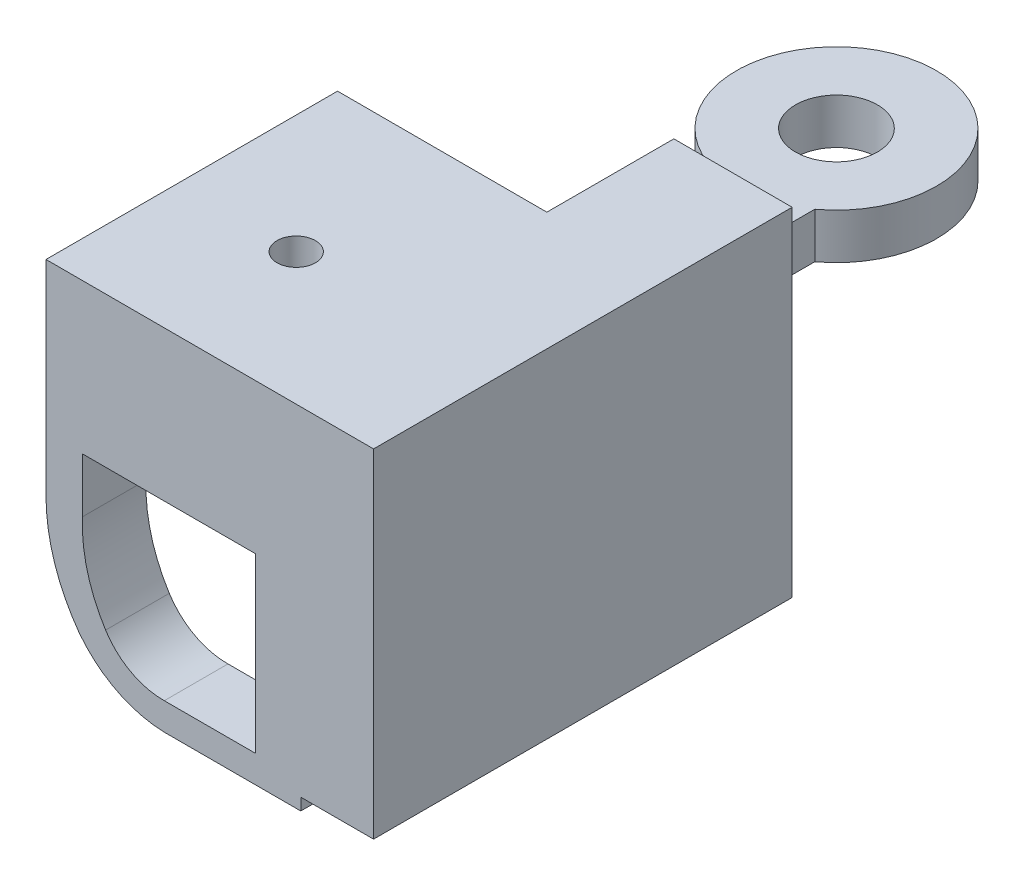
SolidWorks part; units mm, degrees
ref_plane "Front Plane" through (0, 0, 0) normal (0, 0, 1) x (1, 0, 0)
ref_plane "Top Plane" through (0, 0, 0) normal (0, 1, 0) x (1, 0, 0)
ref_plane "Right Plane" through (0, 0, 0) normal (1, 0, 0) x (0, 0, -1)
sketch "Sketch1" plane through (0, 0, 0) normal (0, 0, 1) x (1, 0, 0)
  line L0 (-22.7185, 23.9661) -> (13.2815, 23.9348)
  line L1 (13.2815, 23.9348) -> (13.2815, -13.2108)
  line L2 (-22.7185, 23.9661) -> (-22.7185, 1.4689)
  line L3 (-9.7185, -14.5292) -> (5.2815, -14.5292)
  line L4 (5.2815, -14.5292) -> (5.2815, -13.2108)
  line L5 (5.2815, -13.2108) -> (13.2815, -13.2108)
  line L6 (-18.7185, 7.4681) -> (0.2815, 7.4681)
  line L7 (0.2815, 7.4681) -> (0.2815, -11.5296)
  line L8 (0.2815, -11.5296) -> (-9.7185, -11.5296)
  line L9 (-18.7185, 7.4681) -> (-18.7185, 1.4689)
  arc A0 (-22.7185, 1.4689) -> (-19.057, -9.763) centre (-3.6605, 1.4689) ccw
  arc A1 (-19.057, -9.763) -> (-9.7185, -14.5292) centre (-9.3786, -2.3316) ccw
  arc A2 (-18.7185, 1.4689) -> (-16.1684, -8.0368) centre (-2.2275, 0.798) ccw
  arc A3 (-16.1684, -8.0368) -> (-9.7185, -11.5296) centre (-9.8186, -4.0127) ccw
extrude "Boss-Extrude1" add sketch "Sketch1" along normal blind 46
sketch "Sketch3" plane through (0, -14.5292, 0) normal (0, -1, 0) x (1, 0, 0)
  line L0 (13.2815, 38.1516) -> (-2.7185, 38.1516) construction
  line L7 (13.2815, 46) -> (13.2815, 0) construction
  line L8 (-9.7185, 46) -> (-9.7185, 39) construction
  line L10 (-9.7185, 46) -> (-9.7185, 0) construction
  line L11 (-22.7185, 46) -> (-22.7185, 0) construction
  line L12 (-22.7185, 39) -> (0.2815, 39)
  line L13 (-22.7185, 39) -> (-22.7185, 24)
  line L14 (-22.7185, 24) -> (0.2815, 24)
  line L15 (0.2815, 39) -> (0.2815, 24)
  line L16 (-22.7185, 39) -> (0.2815, 24) construction
  line L17 (-22.7185, 24) -> (0.2815, 39) construction
  point P13 (-11.2185, 31.5)
  dimension "D1" = 15
extrude "Cut-Extrude2" cut sketch "Sketch3" against normal blind 28
sketch "Sketch4" plane through (0, -14.5292, 0) normal (0, -1, 0) x (1, 0, 0)
  line L0 (-9.7185, 24) -> (-9.7185, 14) construction
  line L12 (13.2815, 10.3933) -> (-2.7185, 10.3933) construction
  line L13 (13.2815, 46) -> (13.2815, 0) construction
  line L14 (-22.7185, 24) -> (-22.7185, 0) construction
  line L15 (-22.7185, 13.9579) -> (0.2815, 13.9579)
  line L16 (-22.7185, 13.9579) -> (-22.7185, 0)
  line L17 (-22.7185, 0) -> (0.2815, 0)
  line L18 (0.2815, 13.9579) -> (0.2815, 0)
  line L19 (-22.7185, 13.9579) -> (0.2815, 0) construction
  line L20 (-22.7185, 0) -> (0.2815, 13.9579) construction
  line L21 (-9.7185, 0) -> (5.2815, 0) construction
  line L22 (-9.7185, 24) -> (-9.7185, 0) construction
  point P14 (-11.2185, 6.979)
extrude "Cut-Extrude3" cut sketch "Sketch4" against normal blind 69
ref_plane "Plane1" through (0, 16, 0) normal (0, 1, 0) x (1, 0, 0)
sketch "Sketch8" plane through (-22.7185, 0, 0) normal (-1, 0, 0) x (0, 0, 1)
  line L0 (19.8, 16) -> (-19.8, 16) construction
  line L1 (23.8919, 16) -> (39, 16)
  line L2 (23.8919, 16) -> (23.8919, 13.4708)
  line L3 (23.8919, 13.4708) -> (39, 13.4708)
  line L4 (39, 16) -> (39, 13.4708)
  line L5 (23.8919, 16) -> (39, 13.4708) construction
  line L6 (23.8919, 13.4708) -> (39, 16) construction
  point P4 (31.446, 14.7354)
extrude "Cut-Extrude4" cut sketch "Sketch8" against normal blind 5
sketch "Sketch9" plane through (0, 13.4708, 0) normal (0, -1, 0) x (1, 0, 0)
  line L0 (-9.7185, 39) -> (-9.7185, 24) construction
  line L1 (0.2815, 31.5) -> (-17.7185, 31.5) construction
  line L2 (0.2815, 24) -> (0.2815, 39) construction
  line L3 (-17.7185, 39) -> (-17.7185, 24) construction
  circle A0 centre (-9.7185, 31.5) radius 2.1116
extrude "Cut-Extrude5" cut sketch "Sketch9" against normal blind 22
sketch "Sketch7" plane through (0, 16, 0) normal (0, 1, 0) x (1, 0, 0)
  line L0 (0.2815, 0) -> (0.2815, 6.7902) construction
  circle A0 centre (0.2815, 17.8709) radius 11
  circle A1 centre (0.2815, 17.8709) radius 4.5
  point P4 (0.2815, 17.8709)
extrude "Boss-Extrude2" add sketch "Sketch7" against normal blind 5
sketch "Sketch10" plane through (0, 16, 0) normal (0, 1, 0) x (1, 0, 0)
  line L0 (0.2815, 0) -> (0.2815, 6.8709)
  line L1 (6.7815, 0) -> (6.7815, 8.9968)
  line L2 (13.2815, 0) -> (0.2815, 0) construction
  line L3 (0.2815, 0) -> (6.7815, 0)
  circle A0 centre (0.2815, 17.8709) radius 11 construction
  arc A1 (0.2815, 6.8709) -> (6.7815, 8.9968) centre (0.2815, 17.8709) ccw
extrude "Boss-Extrude3" add sketch "Sketch10" against normal blind 5
